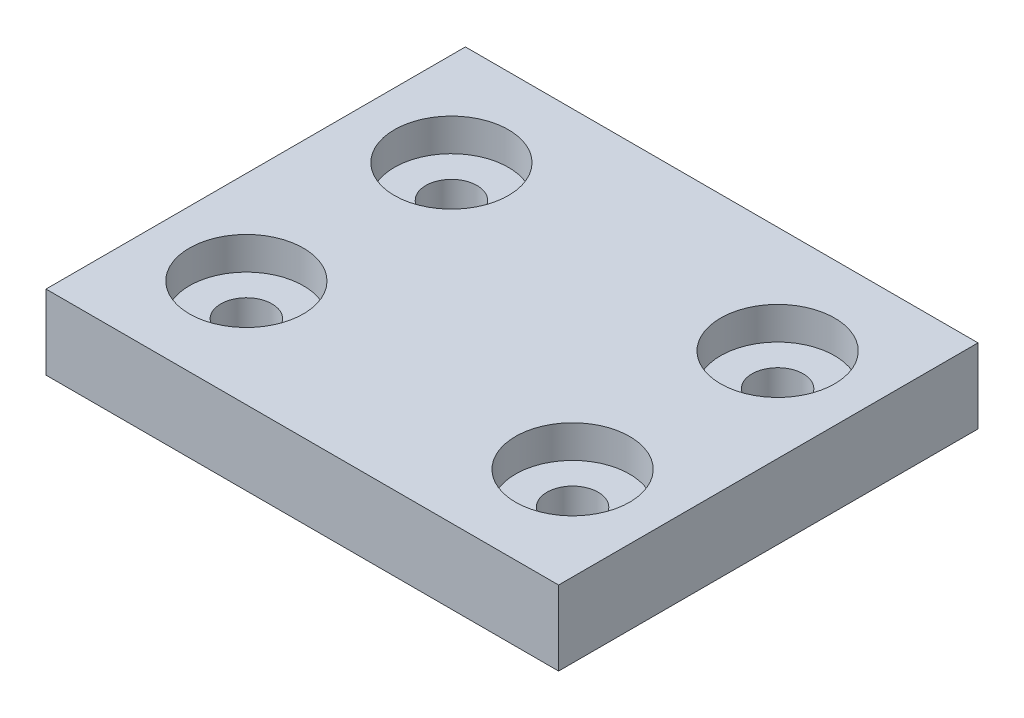
SolidWorks part; units mm, degrees
ref_plane "Front Plane" through (0, 0, 0) normal (0, 0, 1) x (1, 0, 0)
ref_plane "Top Plane" through (0, 0, 0) normal (0, 1, 0) x (1, 0, 0)
ref_plane "Right Plane" through (0, 0, 0) normal (1, 0, 0) x (0, 0, -1)
sketch "Sketch1" plane through (0, 0, 0) normal (0, 1, 0) x (1, 0, 0)
  line L1 (-27.5, 22.5) -> (27.5, 22.5)
  line L2 (-27.5, 22.5) -> (-27.5, -22.5)
  line L3 (-27.5, -22.5) -> (27.5, -22.5)
  line L4 (27.5, 22.5) -> (27.5, -22.5)
  line L5 (-27.5, 22.5) -> (27.5, -22.5) construction
  line L6 (-27.5, -22.5) -> (27.5, 22.5) construction
  point P0 (0, 0)
  dimension "D1" = 55
  dimension "D2" = 45
extrude "Boss-Extrude1" add sketch "Sketch1" along normal blind 8
hole_wizard "CBORE for M5 Hex Head Cap Screw1" positions "Sketch2" profile "Sketch3" counterbore size "M5" standard "ISO" end condition through all
sketch "Sketch2" plane through (0, 8, 0) normal (0, 1, 0) x (1, 0, 0)
  point P0 (-17.5, 11)
  point P2 (17.5, 11)
  point P4 (17.5, -11)
  point P6 (-17.5, -11)
  dimension "D1" = 35
  dimension "D2" = 22
  dimension "D3" = 11
  dimension "D4" = 17.5
sketch "Sketch3" plane through (-17.5, 8, -11) normal (1, 0, 0) x (0, 0, 1)
  line L0 (0, 0) -> (0, 8)
  line L1 (0, 8) -> (2.75, 8)
  line L3 (2.75, 8) -> (2.75, 3.5)
  line L4 (2.75, 3.5) -> (6.119, 3.5)
  line L5 (6.119, 3.5) -> (6.119, 0)
  line L7 (6.119, 0) -> (0, 0)
  line L11 (0, -6.35) -> (0, 107.95) construction
  dimension "Thru Hole Dia." = 5.5
  dimension "Thru Hole Depth" = 8
  dimension "C'Bore Dia." = 12.238
  dimension "C'Bore Depth" = 3.5
